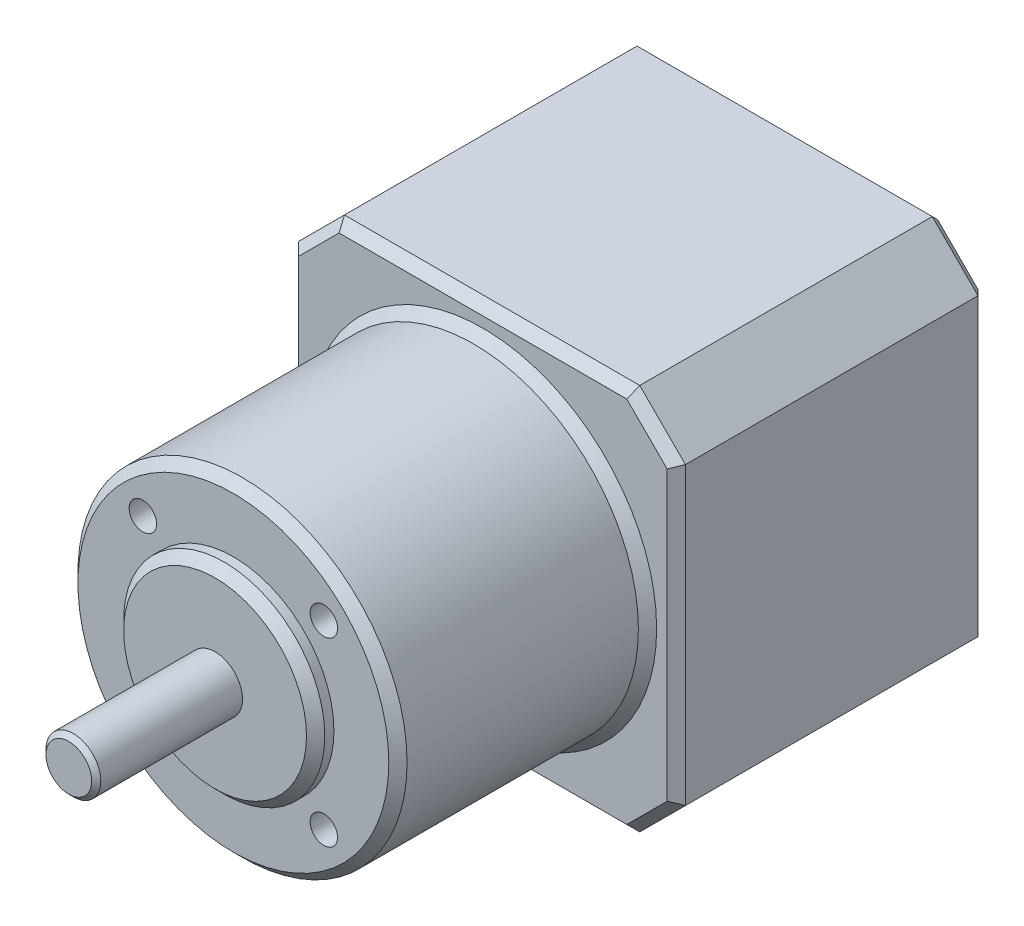
SolidWorks part; units mm, degrees
ref_plane "Front Plane" through (0, 0, 0) normal (0, 0, 1) x (1, 0, 0)
ref_plane "Top Plane" through (0, 0, 0) normal (0, 1, 0) x (1, 0, 0)
ref_plane "Right Plane" through (0, 0, 0) normal (1, 0, 0) x (0, 0, -1)
sketch "Sketch1" plane through (0, 0, 0) normal (0, 0, 1) x (1, 0, 0)
  line L1 (-21.15, 21.15) -> (21.15, 21.15)
  line L2 (-21.15, 21.15) -> (-21.15, -21.15)
  line L3 (-21.15, -21.15) -> (21.15, -21.15)
  line L4 (21.15, 21.15) -> (21.15, -21.15)
  line L5 (-21.15, 21.15) -> (21.15, -21.15) construction
  line L6 (-21.15, -21.15) -> (21.15, 21.15) construction
  point P0 (0, 0)
  dimension "D1" = 42.3
  dimension "D2" = 42.3
extrude "Boss-Extrude1" add sketch "Sketch1" along normal blind 34
chamfer "Chamfer1" distance 5 angle 45 4 edges at (-21.15, -21.15, 17) (-21.15, 21.15, 17) (21.15, -21.15, 17) (21.15, 21.15, 17)
sketch "Sketch2" plane through (0, 0, 34) normal (0, 0, 1) x (1, 0, 0)
  circle A0 centre (0, 0) radius 18
  dimension "D1" = 36
extrude "Boss-Extrude2" add sketch "Sketch2" along normal blind 27.3
sketch "Sketch3" plane through (0, 0, 61.3) normal (0, 0, 1) x (1, 0, 0)
  circle A0 centre (0, 0) radius 11
  dimension "D1" = 22
extrude "Boss-Extrude3" add sketch "Sketch3" along normal blind 2
sketch "Sketch4" plane through (0, 0, 63.3) normal (0, 0, 1) x (1, 0, 0)
  circle A0 centre (0, 0) radius 3
  dimension "D1" = 6
extrude "Boss-Extrude4" add sketch "Sketch4" along normal blind 16
chamfer "Chamfer2" distance 1 angle 45 14 edges at (-18.65, 18.65, 34) (0, 21.15, 34) (21.15, 0, 34) (18.65, -18.65, 34) (0, -21.15, 34) (-18.65, -18.65, 34) (-21.15, 0, 34) (21.15, 0, 0) (18.65, 18.65, 0) (0, 21.15, 0) (-18.65, 18.65, 0) (-21.15, 0, 0) (-18.65, -18.65, 0) (0, -21.15, 0)
chamfer "Chamfer3" distance 0.5 angle 45 1 edges at (3, 0, 79.3)
sketch "Sketch5" plane through (0, 0, 61.3) normal (0, 0, 1) x (1, 0, 0)
  line L0 (0, 0) -> (35.1247, 0) construction
  line L1 (0, 0) -> (25.531, 25.531) construction
  circle A0 centre (9.8995, 9.8995) radius 1.5
  circle A1 centre (9.8995, -9.8995) radius 1.5
  circle A2 centre (-9.8995, -9.8995) radius 1.5
  circle A3 centre (-9.8995, 9.8995) radius 1.5
  point P15 (0, 0)
  dimension "D1" = 3
  dimension "D2" = 45
  dimension "D3" = 14
  dimension "D4" = 4
extrude "Cut-Extrude1" cut sketch "Sketch5" against normal blind 5
scale "Echelle1" scale about centroid uniform scaling yes scale factor 2
scale "Echelle2" scale about centroid uniform scaling yes scale factor 0.25
